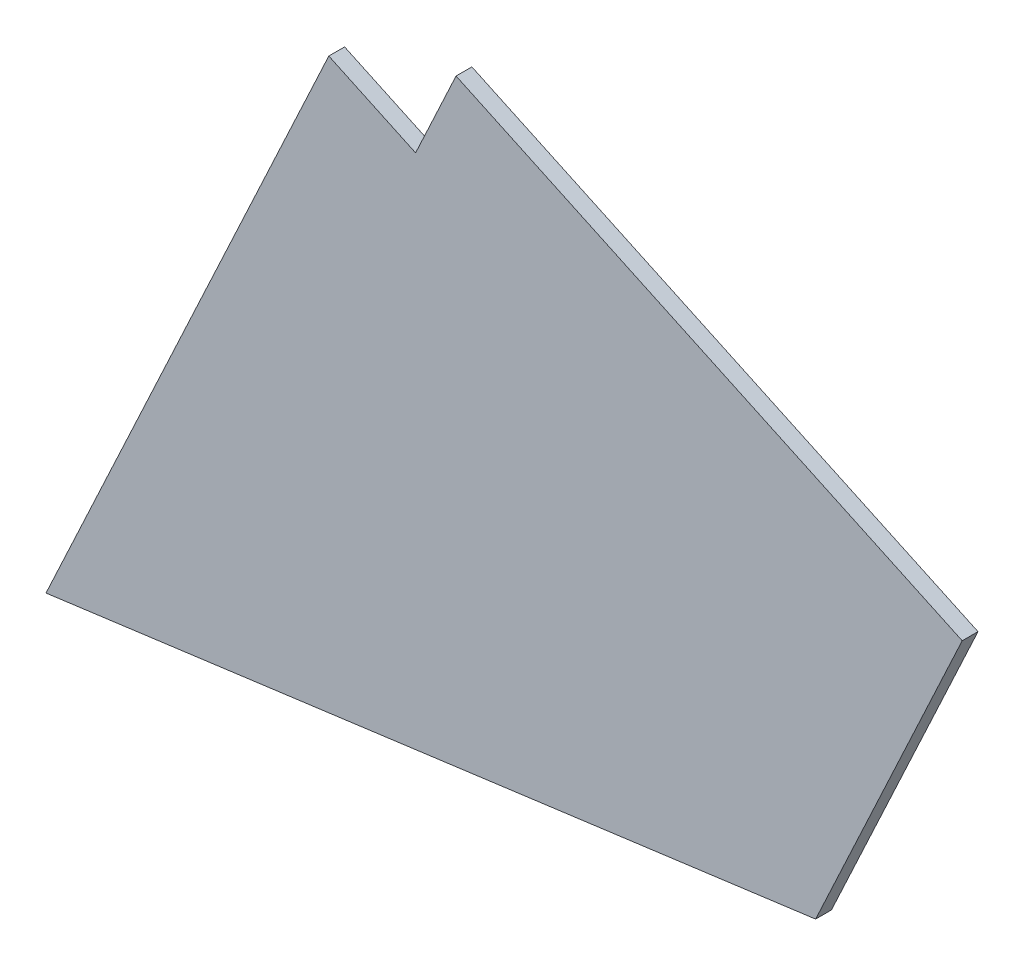
SolidWorks part; units mm, degrees
material "Balsa"
ref_plane "Front Plane" through (0, 0, 0) normal (0, 0, 1) x (1, 0, 0)
ref_plane "Top Plane" through (0, 0, 0) normal (0, 1, 0) x (1, 0, 0)
ref_plane "Right Plane" through (0, 0, 0) normal (1, 0, 0) x (0, 0, -1)
sketch "Sketch1" plane through (0, 0, 396.7) normal (0, 0, 1) x (1, 0, 0)
  line L0 (-344.8461, -37.3321) -> (-184.1003, -15.9367)
  line L1 (-344.8461, -37.3321) -> (-184.1003, -15.9367) construction
  line L2 (-344.8461, -37.3321) -> (-285.7774, 89.341)
  line L3 (-285.7774, 89.341) -> (-267.6513, 80.8887)
  line L4 (-267.6513, 80.8887) -> (-259.1989, 99.0148)
  line L5 (-259.1989, 99.0148) -> (-153.4844, 49.7193)
  line L6 (-153.4844, 49.7193) -> (-184.1003, -15.9367)
  line L8 (-255.5737, 97.3243) -> (63.4467, -51.4373) construction
  line L10 (-327.4362, 0.0035) -> (-285.7774, 89.341) construction
  line L11 (-285.7774, 89.341) -> (-267.6513, 80.8887) construction
  line L12 (-267.6513, 80.8887) -> (-259.1989, 99.0148) construction
  line L13 (-184.1003, -15.9367) -> (-153.4844, 49.7193) construction
extrude "Boss-Extrude1" add sketch "Sketch1" against normal blind 3.3
